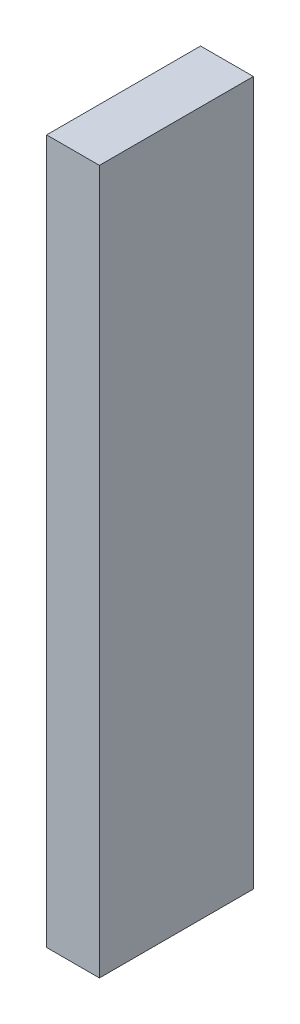
SolidWorks part; units mm, degrees
ref_plane "Top" through (0, 0, 0) normal (0, 0, 1) x (1, 0, 0)
ref_plane "Front" through (0, 0, 0) normal (0, 1, 0) x (1, 0, 0)
ref_plane "Right" through (0, 0, 0) normal (1, 0, 0) x (0, 0, -1)
sketch "Profile Sketch" plane through (-13.8341, 0, -105.7567) normal (0, 1, 0) x (-1, 0, 0)
  line L1 (-3, 0) -> (3, 0)
  line L2 (-3, 0) -> (-3, 17.5)
  line L3 (-3, 17.5) -> (3, 17.5)
  line L4 (3, 0) -> (3, 17.5)
  line L5 (0, 17.5) -> (0, 0) construction
  line L6 (-3, 8.75) -> (3, 8.75) construction
  point P128 (0, 8.75)
  dimension "Height" = 17.5
  dimension "Width" = 6
extrude "Profile Extrude" add sketch "Profile Sketch" along normal blind 80
